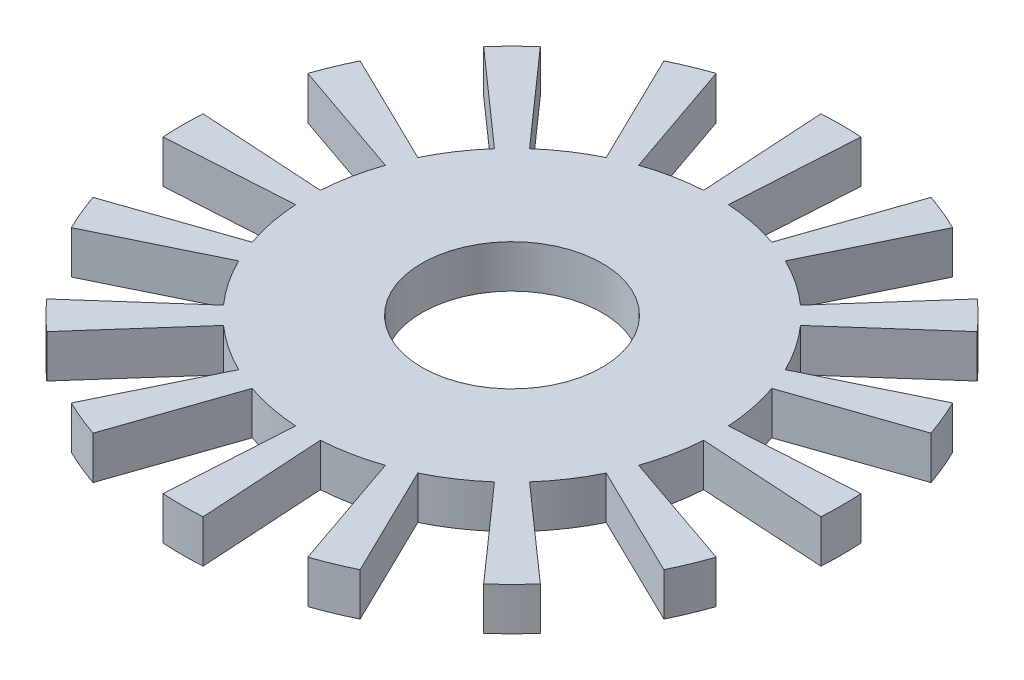
SolidWorks part; units mm, degrees
ref_plane "Front Plane" through (0, 0, 0) normal (0, 0, 1) x (1, 0, 0)
ref_plane "Top Plane" through (0, 0, 0) normal (0, 1, 0) x (1, 0, 0)
ref_plane "Right Plane" through (0, 0, 0) normal (1, 0, 0) x (0, 0, -1)
sketch "Sketch2" plane through (0, 0, 0) normal (0, 1, 0) x (1, 0, 0)
  line L18 (-17.3067, 35.5098) -> (-10.733, 22.022)
  line L20 (-2.4003, 39.4297) -> (-1.4886, 24.453)
  line L22 (12.8715, 37.3468) -> (7.9825, 23.1613)
  line L24 (26.1838, 29.5783) -> (16.2383, 18.3435)
  line L26 (35.5098, 17.3067) -> (22.022, 10.733)
  line L28 (39.4297, 2.4003) -> (24.453, 1.4886)
  line L30 (37.3468, -12.8715) -> (23.1613, -7.9825)
  line L32 (29.5783, -26.1838) -> (18.3435, -16.2383)
  line L34 (17.3067, -35.5098) -> (10.733, -22.022)
  line L36 (2.4003, -39.4297) -> (1.4886, -24.453)
  line L38 (-12.8715, -37.3468) -> (-7.9825, -23.1613)
  line L40 (-26.1838, -29.5783) -> (-16.2383, -18.3435)
  line L42 (-35.5098, -17.3067) -> (-22.022, -10.733)
  line L44 (-39.4297, -2.4003) -> (-24.453, -1.4886)
  line L46 (-37.3468, 12.8715) -> (-23.1613, 7.9825)
  line L48 (-29.5783, 26.1838) -> (-18.3435, 16.2383)
  line L82 (-15.9897, 38.6025) -> (-15.6074, 38.6695)
  line L86 (-22.022, 10.733) -> (-35.5098, 17.3067)
  line L90 (-16.2383, 18.3435) -> (-26.1838, 29.5783)
  line L94 (-7.9825, 23.1613) -> (-12.8715, 37.3468)
  line L98 (1.4886, 24.453) -> (2.4003, 39.4297)
  line L102 (10.733, 22.022) -> (17.3067, 35.5098)
  line L106 (18.3435, 16.2383) -> (29.5783, 26.1838)
  line L110 (23.1613, 7.9825) -> (37.3468, 12.8715)
  line L114 (24.453, -1.4886) -> (39.4297, -2.4003)
  line L118 (22.022, -10.733) -> (35.5098, -17.3067)
  line L122 (16.2383, -18.3435) -> (26.1838, -29.5783)
  line L126 (7.9825, -23.1613) -> (12.8715, -37.3468)
  line L130 (-1.4886, -24.453) -> (-2.4003, -39.4297)
  line L134 (-10.733, -22.022) -> (-17.3067, -35.5098)
  line L138 (-18.3435, -16.2383) -> (-29.5783, -26.1838)
  line L142 (-23.1613, -7.9825) -> (-37.3468, -12.8715)
  line L146 (-24.453, 1.4886) -> (-39.4297, 2.4003)
  circle A0 centre (0, 0) radius 10.8077
  arc A1 (-24.453, -1.4886) -> (-23.1613, -7.9825) centre (0, 0) ccw
  arc A2 (-22.022, -10.733) -> (-18.3435, -16.2383) centre (0, 0) ccw
  arc A3 (-23.1613, 7.9825) -> (-24.453, 1.4886) centre (0, 0) ccw
  arc A4 (-18.3435, 16.2383) -> (-22.022, 10.733) centre (0, 0) ccw
  arc A5 (-10.733, 22.022) -> (-16.2383, 18.3435) centre (0, 0) ccw
  arc A6 (-1.4886, 24.453) -> (-7.9825, 23.1613) centre (0, 0) ccw
  arc A7 (7.9825, 23.1613) -> (1.4886, 24.453) centre (0, 0) ccw
  arc A8 (16.2383, 18.3435) -> (10.733, 22.022) centre (0, 0) ccw
  arc A9 (22.022, 10.733) -> (18.3435, 16.2383) centre (0, 0) ccw
  arc A10 (24.453, 1.4886) -> (23.1613, 7.9825) centre (0, 0) ccw
  arc A11 (23.1613, -7.9825) -> (24.453, -1.4886) centre (0, 0) ccw
  arc A12 (18.3435, -16.2383) -> (22.022, -10.733) centre (0, 0) ccw
  arc A13 (10.733, -22.022) -> (16.2383, -18.3435) centre (0, 0) ccw
  arc A14 (1.4886, -24.453) -> (7.9825, -23.1613) centre (0, 0) ccw
  arc A15 (-7.9825, -23.1613) -> (-1.4886, -24.453) centre (0, 0) ccw
  arc A16 (-16.2383, -18.3435) -> (-10.733, -22.022) centre (0, 0) ccw
  arc A17 (39.4297, -2.4003) -> (39.4297, 2.4003) centre (0, 0) ccw
  arc A18 (35.5098, -17.3067) -> (37.3468, -12.8715) centre (0, 0) ccw
  arc A19 (26.1838, -29.5783) -> (29.5783, -26.1838) centre (0, 0) ccw
  arc A20 (12.8715, -37.3468) -> (17.3067, -35.5098) centre (0, 0) ccw
  arc A21 (-2.4003, -39.4297) -> (2.4003, -39.4297) centre (0, 0) ccw
  arc A22 (-17.3067, -35.5098) -> (-12.8715, -37.3468) centre (0, 0) ccw
  arc A23 (-29.5783, -26.1838) -> (-26.1838, -29.5783) centre (0, 0) ccw
  arc A24 (-37.3468, -12.8715) -> (-35.5098, -17.3067) centre (0, 0) ccw
  arc A25 (-39.4297, 2.4003) -> (-39.4297, -2.4003) centre (0, 0) ccw
  arc A26 (-35.5098, 17.3067) -> (-37.3468, 12.8715) centre (0, 0) ccw
  arc A27 (-26.1838, 29.5783) -> (-29.5783, 26.1838) centre (0, 0) ccw
  arc A28 (-12.8715, 37.3468) -> (-17.3067, 35.5098) centre (0, 0) ccw
  arc A29 (2.4003, 39.4297) -> (-2.4003, 39.4297) centre (0, 0) ccw
  arc A30 (17.3067, 35.5098) -> (12.8715, 37.3468) centre (0, 0) ccw
  arc A31 (29.5783, 26.1838) -> (26.1838, 29.5783) centre (0, 0) ccw
  arc A32 (37.3468, 12.8715) -> (35.5098, 17.3067) centre (0, 0) ccw
  point P39 (0, 0)
  point P73 (0, 0)
  dimension "D1" = 21.6154
  dimension "D4" = 48.9966
  dimension "D7" = 16
extrude "Boss-Extrude1" add sketch "Sketch2" along normal blind 5.1308
